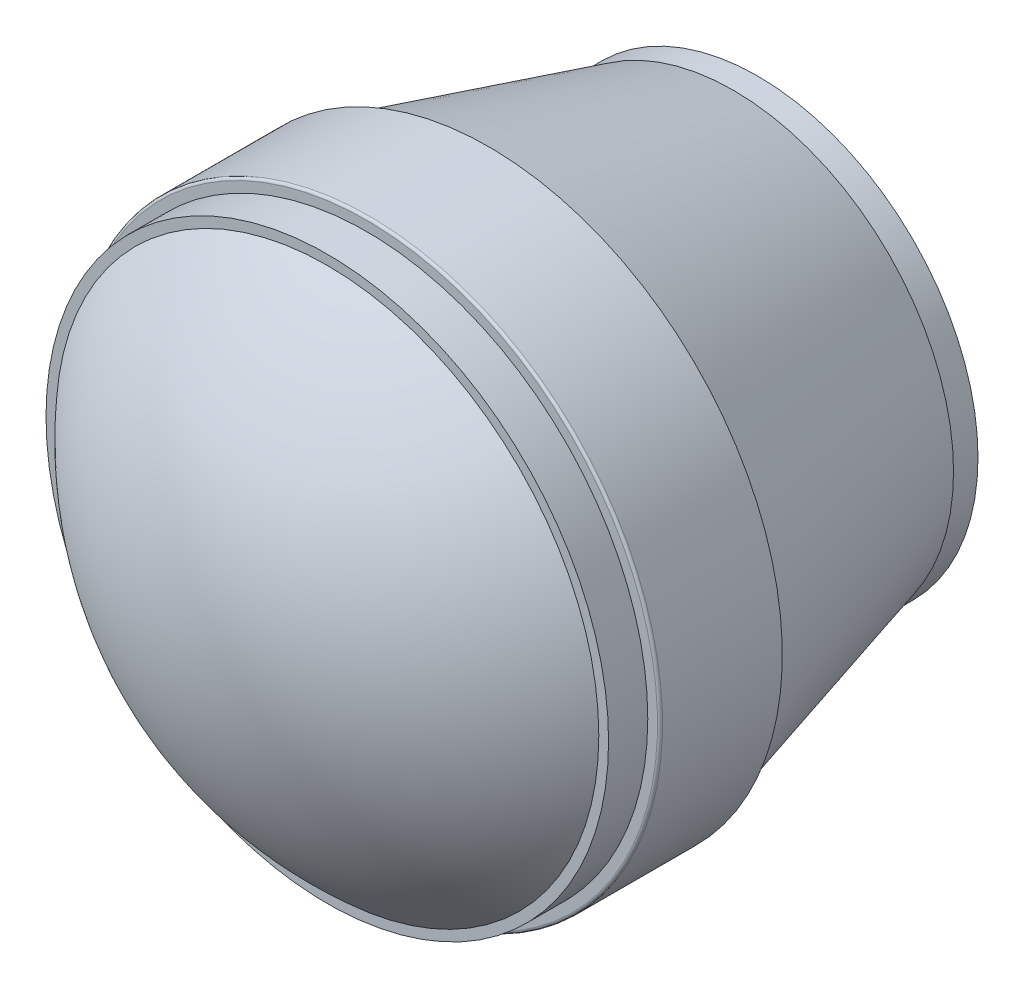
SolidWorks part; units mm, degrees
ref_plane "Front Plane" through (0, 0, 0) normal (0, 0, 1) x (1, 0, 0)
ref_plane "Top Plane" through (0, 0, 0) normal (0, 1, 0) x (1, 0, 0)
ref_plane "Right Plane" through (0, 0, 0) normal (1, 0, 0) x (0, 0, -1)
curve "S1"
  spline degree 3 poles (0, 0, 0) (0, 0.0167, 0) (0, 0.05, -0.0001) (0, 0.1, -0.0007) (0, 0.15, -0.0015) (0, 0.2, -0.0028) (0, 0.25, -0.0044) (0, 0.3, -0.0063) (0, 0.35, -0.0087) (0, 0.4, -0.0113) (0, 0.45, -0.0143) (0, 0.5, -0.0177) (0, 0.55, -0.0215) (0, 0.6, -0.0255) (0, 0.65, -0.03) (0, 0.7, -0.0348) (0, 0.75, -0.04) (0, 0.8, -0.0455) (0, 0.85, -0.0514) (0, 0.9, -0.0577) (0, 0.95, -0.0643) (0, 1, -0.0713) (0, 1.05, -0.0786) (0, 1.1, -0.0863) (0, 1.15, -0.0944) (0, 1.2, -0.1028) (0, 1.25, -0.1116) (0, 1.3, -0.1208) (0, 1.35, -0.1303) (0, 1.4, -0.1402) (0, 1.45, -0.1505) (0, 1.5, -0.1612) (0, 1.55, -0.1722) (0, 1.6, -0.1836) (0, 1.65, -0.1954) (0, 1.7, -0.2075) (0, 1.75, -0.2201) (0, 1.8, -0.233) (0, 1.85, -0.2463) (0, 1.9001, -0.26) (0, 1.9501, -0.274) (0, 2.0001, -0.2885) (0, 2.0501, -0.3034) (0, 2.1001, -0.3186) (0, 2.1501, -0.3342) (0, 2.2001, -0.3503) (0, 2.2501, -0.3667) (0, 2.3001, -0.3835) (0, 2.3501, -0.4007) (0, 2.4001, -0.4184) (0, 2.4501, -0.4364) (0, 2.5001, -0.4549) (0, 2.5501, -0.4737) (0, 2.6001, -0.493) (0, 2.6501, -0.5127) (0, 2.7001, -0.5328) (0, 2.7501, -0.5534) (0, 2.8001, -0.5743) (0, 2.8501, -0.5958) (0, 2.9001, -0.6176) (0, 2.9501, -0.6399) (0, 3.0001, -0.6626) (0, 3.0501, -0.6857) (0, 3.1001, -0.7093) (0, 3.1501, -0.7334) (0, 3.2001, -0.7579) (0, 3.2501, -0.7829) (0, 3.3001, -0.8083) (0, 3.3501, -0.8343) (0, 3.4001, -0.8606) (0, 3.4501, -0.8875) (0, 3.5001, -0.9149) (0, 3.5501, -0.9427) (0, 3.6001, -0.971) (0, 3.6501, -0.9999) (0, 3.7001, -1.0292) (0, 3.7501, -1.0591) (0, 3.8001, -1.0895) (0, 3.8501, -1.1204) (0, 3.9001, -1.1518) (0, 3.9501, -1.1838) (0, 4.0001, -1.2164) (0, 4.0501, -1.2494) (0, 4.1001, -1.2831) (0, 4.1501, -1.3173) (0, 4.2001, -1.3521) (0, 4.2501, -1.3875) (0, 4.3001, -1.4235) (0, 4.3501, -1.4601) (0, 4.4002, -1.4973) (0, 4.4502, -1.5351) (0, 4.5002, -1.5736) (0, 4.5502, -1.6127) (0, 4.6002, -1.6525) (0, 4.6502, -1.693) (0, 4.7002, -1.7342) (0, 4.7502, -1.776) (0, 4.8002, -1.8186) (0, 4.8502, -1.8619) (0, 4.9002, -1.9059) (0, 4.9502, -1.9508) (0, 5.0002, -1.9963) (0, 5.0502, -2.0428) (0, 5.1002, -2.09) (0, 5.1502, -2.138) (0, 5.2002, -2.187) (0, 5.2502, -2.2368) (0, 5.3002, -2.2875) (0, 5.3502, -2.3392) (0, 5.4003, -2.3919) (0, 5.4503, -2.4456) (0, 5.5003, -2.5003) (0, 5.5334, -2.5374) (0, 5.55, -2.556) knots 0 0 0 0 0.007943 0.015886 0.02383 0.031776 0.039723 0.047672 0.055623 0.063577 0.071534 0.079495 0.08746 0.09543 0.103404 0.111384 0.119369 0.12736 0.135358 0.143363 0.151375 0.159395 0.167423 0.175459 0.183505 0.19156 0.199625 0.2077 0.215786 0.223884 0.231993 0.240114 0.248248 0.256394 0.264555 0.272729 0.280918 0.289121 0.29734 0.305575 0.313826 0.322095 0.330381 0.338684 0.347006 0.355347 0.363708 0.372088 0.380489 0.388912 0.397356 0.405822 0.414312 0.422825 0.431362 0.439923 0.44851 0.457123 0.465764 0.474431 0.483126 0.49185 0.500603 0.509387 0.518202 0.527047 0.535926 0.544838 0.553785 0.562766 0.571783 0.580837 0.589928 0.599058 0.608228 0.617438 0.626689 0.635983 0.645321 0.654704 0.664133 0.673608 0.683132 0.692706 0.702331 0.712009 0.721739 0.731526 0.741368 0.751269 0.76123 0.771252 0.781338 0.791489 0.801707 0.811995 0.822352 0.832784 0.843291 0.853876 0.864543 0.875292 0.886128 0.897052 0.908069 0.919182 0.930395 0.94171 0.953134 0.964669 0.976322 0.988097 1 1 1 1
curve "S2"
  spline degree 3 poles (0, 0, -10) (0, 0.0167, -10.0001) (0, 0.05, -10.0002) (0, 0.1, -10.0011) (0, 0.15, -10.0026) (0, 0.2, -10.0047) (0, 0.25, -10.0074) (0, 0.3, -10.0108) (0, 0.35, -10.0147) (0, 0.4, -10.0192) (0, 0.45, -10.0244) (0, 0.5, -10.0301) (0, 0.55, -10.0365) (0, 0.6, -10.0435) (0, 0.65, -10.0511) (0, 0.7001, -10.0593) (0, 0.7501, -10.0681) (0, 0.8001, -10.0775) (0, 0.8501, -10.0875) (0, 0.9001, -10.0982) (0, 0.9501, -10.1095) (0, 1.0001, -10.1214) (0, 1.0501, -10.1339) (0, 1.1001, -10.147) (0, 1.1501, -10.1608) (0, 1.2001, -10.1752) (0, 1.2501, -10.1902) (0, 1.3001, -10.2058) (0, 1.3501, -10.2221) (0, 1.4001, -10.239) (0, 1.4501, -10.2565) (0, 1.5001, -10.2747) (0, 1.5501, -10.2935) (0, 1.6001, -10.3129) (0, 1.6501, -10.333) (0, 1.7001, -10.3537) (0, 1.7501, -10.375) (0, 1.8001, -10.397) (0, 1.8501, -10.4196) (0, 1.9001, -10.4429) (0, 1.9501, -10.4668) (0, 2.0001, -10.4913) (0, 2.0501, -10.5165) (0, 2.1001, -10.5424) (0, 2.1501, -10.569) (0, 2.2001, -10.5962) (0, 2.2501, -10.624) (0, 2.3002, -10.6526) (0, 2.3502, -10.6819) (0, 2.4002, -10.7119) (0, 2.4502, -10.7426) (0, 2.5002, -10.774) (0, 2.5502, -10.8062) (0, 2.6002, -10.8392) (0, 2.6502, -10.8729) (0, 2.7002, -10.9076) (0, 2.7502, -10.943) (0, 2.8002, -10.9794) (0, 2.8502, -11.0167) (0, 2.9003, -11.055) (0, 2.9503, -11.0944) (0, 3.0003, -11.1349) (0, 3.0503, -11.1766) (0, 3.1003, -11.2197) (0, 3.1504, -11.2641) (0, 3.2005, -11.31) (0, 3.2334, -11.3416) (0, 3.25, -11.3575) knots 0 0 0 0 0.013871 0.027745 0.041622 0.055505 0.069397 0.083299 0.097213 0.111141 0.125085 0.139048 0.15303 0.167036 0.181065 0.195122 0.209207 0.223322 0.23747 0.251652 0.265872 0.28013 0.294429 0.308771 0.323157 0.337592 0.352074 0.366608 0.381194 0.395836 0.410535 0.425292 0.44011 0.454991 0.469937 0.484949 0.50003 0.515182 0.530405 0.545705 0.561079 0.576533 0.592068 0.607687 0.623389 0.639181 0.655063 0.671039 0.687112 0.703284 0.71956 0.735945 0.752442 0.769056 0.785794 0.802664 0.81967 0.836822 0.854131 0.871607 0.889262 0.907113 0.925175 0.94347 0.962021 0.980852 1 1 1 1
sketch "Sketch1" plane through (0, 0, 0) normal (1, 0, 0) x (0, 0, -1)
  line L0 (10, 0) -> (0, 0)
  line L1 (3.3575, 5.75) -> (2.556, 5.75)
  line L2 (3.4083, 6) -> (5.8575, 6)
  line L3 (3.3575, 5.75) -> (3.3575, 5.9492)
  line L4 (0, 0) -> (0, -6.5315) construction
  line L5 (2.556, 5.75) -> (2.556, 5.55)
  line L7 (11.887, 0) -> (-0.8091, 0) construction
  line L8 (11.3575, 3.25) -> (11.3575, 4.5)
  line L11 (5.8575, 6) -> (5.8575, 5.873)
  line L12 (5.8575, 5.873) -> (10.8575, 4.5)
  line L13 (10.8575, 4.5) -> (11.3575, 4.5)
  line L14 (10.8392, 2.6) -> (2.3918, 5.4) construction
  arc A0 (3.3575, 5.9492) -> (3.4083, 6) centre (3.4083, 5.9492) cw
  spline S0 degree 3 poles (-1989.9068, 6.7041) (18.0008, -8.3631) (9.9215, -4.1008) (10.0011, 0.1) (10.0026, 0.15) (10.0047, 0.2) (10.0074, 0.25) (10.0108, 0.3) (10.0147, 0.35) (10.0192, 0.4) (10.0244, 0.45) (10.0301, 0.5) (10.0365, 0.55) (10.0435, 0.6) (10.0511, 0.65) (10.0593, 0.7001) (10.0681, 0.7501) (10.0775, 0.8001) (10.0875, 0.8501) (10.0982, 0.9001) (10.1095, 0.9501) (10.1214, 1.0001) (10.1339, 1.0501) (10.147, 1.1001) (10.1608, 1.1501) (10.1752, 1.2001) (10.1902, 1.2501) (10.2058, 1.3001) (10.2221, 1.3501) (10.239, 1.4001) (10.2565, 1.4501) (10.2747, 1.5001) (10.2935, 1.5501) (10.3129, 1.6001) (10.333, 1.6501) (10.3537, 1.7001) (10.375, 1.7501) (10.397, 1.8001) (10.4196, 1.8501) (10.4429, 1.9001) (10.4668, 1.9501) (10.4913, 2.0001) (10.5165, 2.0501) (10.5424, 2.1001) (10.569, 2.1501) (10.5962, 2.2001) (10.624, 2.2501) (10.6526, 2.3002) (10.6819, 2.3502) (10.7119, 2.4002) (10.7426, 2.4502) (10.774, 2.5002) (10.8062, 2.5502) (10.8392, 2.6002) (10.8729, 2.6502) (10.9076, 2.7002) (10.943, 2.7502) (10.9794, 2.8002) (11.0167, 2.8502) (11.055, 2.9003) (11.0944, 2.9503) (11.1349, 3.0003) (11.1766, 3.0503) (11.2197, 3.1003) (11.2641, 3.1504) (14.3554, 6.5254) (25.0141, 2.7467) (-1435.5515, 1383.7984) knots -3.455054 -3.455054 -3.455054 -3.455054 0.013871 0.027745 0.041622 0.055505 0.069397 0.083299 0.097213 0.111141 0.125085 0.139048 0.15303 0.167036 0.181065 0.195122 0.209207 0.223322 0.23747 0.251652 0.265872 0.28013 0.294429 0.308771 0.323157 0.337592 0.352074 0.366608 0.381194 0.395836 0.410535 0.425292 0.44011 0.454991 0.469937 0.484949 0.50003 0.515182 0.530405 0.545705 0.561079 0.576533 0.592068 0.607687 0.623389 0.639181 0.655063 0.671039 0.687112 0.703284 0.71956 0.735945 0.752442 0.769056 0.785794 0.802664 0.81967 0.836822 0.854131 0.871607 0.889262 0.907113 0.925175 0.94347 0.962021 0.980852 4.752308 4.752308 4.752308 4.752308 only from (10, 0) to (11.3575, 3.25) construction
  spline S1 degree 3 poles (-1999.9614, -4.0492) (6.6189, -10.0593) (-0.0547, -4.9695) (0.0007, 0.1) (0.0015, 0.15) (0.0028, 0.2) (0.0044, 0.25) (0.0063, 0.3) (0.0087, 0.35) (0.0113, 0.4) (0.0143, 0.45) (0.0177, 0.5) (0.0215, 0.55) (0.0255, 0.6) (0.03, 0.65) (0.0348, 0.7) (0.04, 0.75) (0.0455, 0.8) (0.0514, 0.85) (0.0577, 0.9) (0.0643, 0.95) (0.0713, 1) (0.0786, 1.05) (0.0863, 1.1) (0.0944, 1.15) (0.1028, 1.2) (0.1116, 1.25) (0.1208, 1.3) (0.1303, 1.35) (0.1402, 1.4) (0.1505, 1.45) (0.1612, 1.5) (0.1722, 1.55) (0.1836, 1.6) (0.1954, 1.65) (0.2075, 1.7) (0.2201, 1.75) (0.233, 1.8) (0.2463, 1.85) (0.26, 1.9001) (0.274, 1.9501) (0.2885, 2.0001) (0.3034, 2.0501) (0.3186, 2.1001) (0.3342, 2.1501) (0.3503, 2.2001) (0.3667, 2.2501) (0.3835, 2.3001) (0.4007, 2.3501) (0.4184, 2.4001) (0.4364, 2.4501) (0.4549, 2.5001) (0.4737, 2.5501) (0.493, 2.6001) (0.5127, 2.6501) (0.5328, 2.7001) (0.5534, 2.7501) (0.5743, 2.8001) (0.5958, 2.8501) (0.6176, 2.9001) (0.6399, 2.9501) (0.6626, 3.0001) (0.6857, 3.0501) (0.7093, 3.1001) (0.7334, 3.1501) (0.7579, 3.2001) (0.7829, 3.2501) (0.8083, 3.3001) (0.8343, 3.3501) (0.8606, 3.4001) (0.8875, 3.4501) (0.9149, 3.5001) (0.9427, 3.5501) (0.971, 3.6001) (0.9999, 3.6501) (1.0292, 3.7001) (1.0591, 3.7501) (1.0895, 3.8001) (1.1204, 3.8501) (1.1518, 3.9001) (1.1838, 3.9501) (1.2164, 4.0001) (1.2494, 4.0501) (1.2831, 4.1001) (1.3173, 4.1501) (1.3521, 4.2001) (1.3875, 4.2501) (1.4235, 4.3001) (1.4601, 4.3501) (1.4973, 4.4002) (1.5351, 4.4502) (1.5736, 4.5002) (1.6127, 4.5502) (1.6525, 4.6002) (1.693, 4.6502) (1.7342, 4.7002) (1.776, 4.7502) (1.8186, 4.8002) (1.8619, 4.8502) (1.9059, 4.9002) (1.9508, 4.9502) (1.9963, 5.0002) (2.0428, 5.0502) (2.09, 5.1002) (2.138, 5.1502) (2.187, 5.2002) (2.2368, 5.2502) (2.2875, 5.3002) (2.3392, 5.3502) (2.3919, 5.4003) (2.4456, 5.4503) (6.8086, 9.4415) (16.9781, 6.9522) (-1323.083, 1502.9243) knots -2.392247 -2.392247 -2.392247 -2.392247 0.007943 0.015886 0.02383 0.031776 0.039723 0.047672 0.055623 0.063577 0.071534 0.079495 0.08746 0.09543 0.103404 0.111384 0.119369 0.12736 0.135358 0.143363 0.151375 0.159395 0.167423 0.175459 0.183505 0.19156 0.199625 0.2077 0.215786 0.223884 0.231993 0.240114 0.248248 0.256394 0.264555 0.272729 0.280918 0.289121 0.29734 0.305575 0.313826 0.322095 0.330381 0.338684 0.347006 0.355347 0.363708 0.372088 0.380489 0.388912 0.397356 0.405822 0.414312 0.422825 0.431362 0.439923 0.44851 0.457123 0.465764 0.474431 0.483126 0.49185 0.500603 0.509387 0.518202 0.527047 0.535926 0.544838 0.553785 0.562766 0.571783 0.580837 0.589928 0.599058 0.608228 0.617438 0.626689 0.635983 0.645321 0.654704 0.664133 0.673608 0.683132 0.692706 0.702331 0.712009 0.721739 0.731526 0.741368 0.751269 0.76123 0.771252 0.781338 0.791489 0.801707 0.811995 0.822352 0.832784 0.843291 0.853876 0.864543 0.875292 0.886128 0.897052 0.908069 0.919182 0.930395 0.94171 0.953134 0.964669 0.976322 0.988097 3.782672 3.782672 3.782672 3.782672 only from (0, 0) to (2.556, 5.55) construction
  spline S3 degree 3 poles (0, 0) (0, 0.0167) (0.0001, 0.05) (0.0007, 0.1) (0.0015, 0.15) (0.0028, 0.2) (0.0044, 0.25) (0.0063, 0.3) (0.0087, 0.35) (0.0113, 0.4) (0.0143, 0.45) (0.0177, 0.5) (0.0215, 0.55) (0.0255, 0.6) (0.03, 0.65) (0.0348, 0.7) (0.04, 0.75) (0.0455, 0.8) (0.0514, 0.85) (0.0577, 0.9) (0.0643, 0.95) (0.0713, 1) (0.0786, 1.05) (0.0863, 1.1) (0.0944, 1.15) (0.1028, 1.2) (0.1116, 1.25) (0.1208, 1.3) (0.1303, 1.35) (0.1402, 1.4) (0.1505, 1.45) (0.1612, 1.5) (0.1722, 1.55) (0.1836, 1.6) (0.1954, 1.65) (0.2075, 1.7) (0.2201, 1.75) (0.233, 1.8) (0.2463, 1.85) (0.26, 1.9001) (0.274, 1.9501) (0.2885, 2.0001) (0.3034, 2.0501) (0.3186, 2.1001) (0.3342, 2.1501) (0.3503, 2.2001) (0.3667, 2.2501) (0.3835, 2.3001) (0.4007, 2.3501) (0.4184, 2.4001) (0.4364, 2.4501) (0.4549, 2.5001) (0.4737, 2.5501) (0.493, 2.6001) (0.5127, 2.6501) (0.5328, 2.7001) (0.5534, 2.7501) (0.5743, 2.8001) (0.5958, 2.8501) (0.6176, 2.9001) (0.6399, 2.9501) (0.6626, 3.0001) (0.6857, 3.0501) (0.7093, 3.1001) (0.7334, 3.1501) (0.7579, 3.2001) (0.7829, 3.2501) (0.8083, 3.3001) (0.8343, 3.3501) (0.8606, 3.4001) (0.8875, 3.4501) (0.9149, 3.5001) (0.9427, 3.5501) (0.971, 3.6001) (0.9999, 3.6501) (1.0292, 3.7001) (1.0591, 3.7501) (1.0895, 3.8001) (1.1204, 3.8501) (1.1518, 3.9001) (1.1838, 3.9501) (1.2164, 4.0001) (1.2494, 4.0501) (1.2831, 4.1001) (1.3173, 4.1501) (1.3521, 4.2001) (1.3875, 4.2501) (1.4235, 4.3001) (1.4601, 4.3501) (1.4973, 4.4002) (1.5351, 4.4502) (1.5736, 4.5002) (1.6127, 4.5502) (1.6525, 4.6002) (1.693, 4.6502) (1.7342, 4.7002) (1.776, 4.7502) (1.8186, 4.8002) (1.8619, 4.8502) (1.9059, 4.9002) (1.9508, 4.9502) (1.9963, 5.0002) (2.0428, 5.0502) (2.09, 5.1002) (2.138, 5.1502) (2.187, 5.2002) (2.2368, 5.2502) (2.2875, 5.3002) (2.3392, 5.3502) (2.3919, 5.4003) (2.4456, 5.4503) (2.5003, 5.5003) (2.5374, 5.5334) (2.556, 5.55) knots 0 0 0 0 0.007943 0.015886 0.02383 0.031776 0.039723 0.047672 0.055623 0.063577 0.071534 0.079495 0.08746 0.09543 0.103404 0.111384 0.119369 0.12736 0.135358 0.143363 0.151375 0.159395 0.167423 0.175459 0.183505 0.19156 0.199625 0.2077 0.215786 0.223884 0.231993 0.240114 0.248248 0.256394 0.264555 0.272729 0.280918 0.289121 0.29734 0.305575 0.313826 0.322095 0.330381 0.338684 0.347006 0.355347 0.363708 0.372088 0.380489 0.388912 0.397356 0.405822 0.414312 0.422825 0.431362 0.439923 0.44851 0.457123 0.465764 0.474431 0.483126 0.49185 0.500603 0.509387 0.518202 0.527047 0.535926 0.544838 0.553785 0.562766 0.571783 0.580837 0.589928 0.599058 0.608228 0.617438 0.626689 0.635983 0.645321 0.654704 0.664133 0.673608 0.683132 0.692706 0.702331 0.712009 0.721739 0.731526 0.741368 0.751269 0.76123 0.771252 0.781338 0.791489 0.801707 0.811995 0.822352 0.832784 0.843291 0.853876 0.864543 0.875292 0.886128 0.897052 0.908069 0.919182 0.930395 0.94171 0.953134 0.964669 0.976322 0.988097 1 1 1 1
  spline S4 degree 3 poles (10, 0) (10.0001, 0.0167) (10.0002, 0.05) (10.0011, 0.1) (10.0026, 0.15) (10.0047, 0.2) (10.0074, 0.25) (10.0108, 0.3) (10.0147, 0.35) (10.0192, 0.4) (10.0244, 0.45) (10.0301, 0.5) (10.0365, 0.55) (10.0435, 0.6) (10.0511, 0.65) (10.0593, 0.7001) (10.0681, 0.7501) (10.0775, 0.8001) (10.0875, 0.8501) (10.0982, 0.9001) (10.1095, 0.9501) (10.1214, 1.0001) (10.1339, 1.0501) (10.147, 1.1001) (10.1608, 1.1501) (10.1752, 1.2001) (10.1902, 1.2501) (10.2058, 1.3001) (10.2221, 1.3501) (10.239, 1.4001) (10.2565, 1.4501) (10.2747, 1.5001) (10.2935, 1.5501) (10.3129, 1.6001) (10.333, 1.6501) (10.3537, 1.7001) (10.375, 1.7501) (10.397, 1.8001) (10.4196, 1.8501) (10.4429, 1.9001) (10.4668, 1.9501) (10.4913, 2.0001) (10.5165, 2.0501) (10.5424, 2.1001) (10.569, 2.1501) (10.5962, 2.2001) (10.624, 2.2501) (10.6526, 2.3002) (10.6819, 2.3502) (10.7119, 2.4002) (10.7426, 2.4502) (10.774, 2.5002) (10.8062, 2.5502) (10.8392, 2.6002) (10.8729, 2.6502) (10.9076, 2.7002) (10.943, 2.7502) (10.9794, 2.8002) (11.0167, 2.8502) (11.055, 2.9003) (11.0944, 2.9503) (11.1349, 3.0003) (11.1766, 3.0503) (11.2197, 3.1003) (11.2641, 3.1504) (11.31, 3.2005) (11.3416, 3.2334) (11.3575, 3.25) knots 0 0 0 0 0.013871 0.027745 0.041622 0.055505 0.069397 0.083299 0.097213 0.111141 0.125085 0.139048 0.15303 0.167036 0.181065 0.195122 0.209207 0.223322 0.23747 0.251652 0.265872 0.28013 0.294429 0.308771 0.323157 0.337592 0.352074 0.366608 0.381194 0.395836 0.410535 0.425292 0.44011 0.454991 0.469937 0.484949 0.50003 0.515182 0.530405 0.545705 0.561079 0.576533 0.592068 0.607687 0.623389 0.639181 0.655063 0.671039 0.687112 0.703284 0.71956 0.735945 0.752442 0.769056 0.785794 0.802664 0.81967 0.836822 0.854131 0.871607 0.889262 0.907113 0.925175 0.94347 0.962021 0.980852 1 1 1 1
  point P21 (3.3575, 6)
  dimension "D19" = 0.0508
  dimension "D2" = 12
  dimension "D3" = 10
  dimension "D4" = 11.5
  dimension "D5" = 6.6425
  dimension "D6" = 2.5
  dimension "D7" = 15.355
  dimension "D8" = 0.127
  dimension "D10" = 0.5
  dimension "D13" = 5.8575
  dimension "D15" = 8
  dimension "D16" = 5.2
  dimension "D17" = 10.8
  dimension "D18" = 9
revolve "Revolve1" add sketch "Sketch1" angle 360 about L7
sketch "Sketch2" plane through (0, 0, -5.8575) normal (0, 0, 1) x (1, 0, 0)
  line L0 (0, 0) -> (9.2, 0) construction
  line L1 (9.2, -1.5) -> (9.2, 1.5)
  line L2 (9.2, 1.5) -> (4.5, 2.3633)
  line L3 (4.5, 2.3633) -> (4.5, -2.3633)
  line L4 (9.2, -1.5) -> (4.5, -2.3633)
  circle A1 centre (0, 0) radius 6 construction
  circle A2 centre (0, 0) radius 4.5 construction
  point P10 (4.5, 0)
  dimension "D1" = 3
  dimension "D2" = 20.817
  dimension "D3" = 3.2
extrude "GATE" [suppressed] add sketch "Sketch2" against normal blind 4
draft "Draft1" [suppressed] type of draft neutral plane draft angle 3 faces to draft 2 parameters "D1"=3
fillet "Fillet1" [suppressed] radius 1
